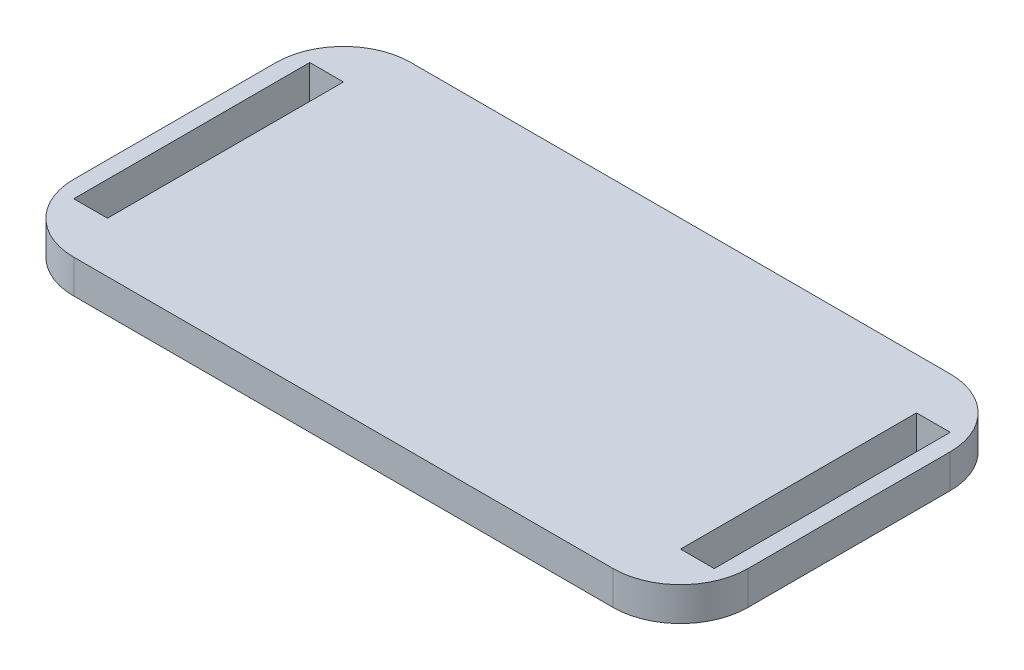
SolidWorks part; units mm, degrees
ref_plane "Alzado" through (0, 0, 0) normal (0, 0, 1) x (1, 0, 0)
ref_plane "Planta" through (0, 0, 0) normal (0, 1, 0) x (1, 0, 0)
ref_plane "Vista lateral" through (0, 0, 0) normal (1, 0, 0) x (0, 0, -1)
sketch "Croquis1" plane through (0, 0, 0) normal (0, 1, 0) x (1, 0, 0)
  line L0 (-50, 0) -> (50, 0) construction
  line L1 (-40, -25) -> (40, -25)
  line L2 (-50, -15) -> (-50, 15)
  line L3 (-40, 25) -> (40, 25)
  line L4 (50, -15) -> (50, 15)
  line L5 (-50, -25) -> (50, 25) construction
  line L6 (-50, 25) -> (50, -25) construction
  line L8 (-47.5, -17.5) -> (-42.5, -17.5)
  line L9 (-47.5, -17.5) -> (-47.5, 17.5)
  line L10 (-47.5, 17.5) -> (-42.5, 17.5)
  line L11 (-42.5, -17.5) -> (-42.5, 17.5)
  line L12 (-47.5, -17.5) -> (-42.5, 17.5) construction
  line L13 (-47.5, 17.5) -> (-42.5, -17.5) construction
  line L14 (42.5, -17.5) -> (47.5, -17.5)
  line L15 (42.5, -17.5) -> (42.5, 17.5)
  line L16 (42.5, 17.5) -> (47.5, 17.5)
  line L17 (47.5, -17.5) -> (47.5, 17.5)
  line L18 (42.5, -17.5) -> (47.5, 17.5) construction
  line L19 (42.5, 17.5) -> (47.5, -17.5) construction
  arc A0 (40, 25) -> (50, 15) centre (40, 15) cw
  arc A1 (40, -25) -> (50, -15) centre (40, -15) ccw
  arc A2 (-40, -25) -> (-50, -15) centre (-40, -15) cw
  arc A3 (-50, 15) -> (-40, 25) centre (-40, 15) cw
  point P0 (0, 0)
  point P8 (-45, 0)
  point P13 (45, 0)
  dimension "D8" = 10
  dimension "D1" = 50
  dimension "D2" = 100
  dimension "D3" = 90
  dimension "D4" = 45
  dimension "D5" = 35
  dimension "D6" = 5
  dimension "D7" = 5
extrude "Saliente-Extruir2" add sketch "Croquis1" along normal blind 5
